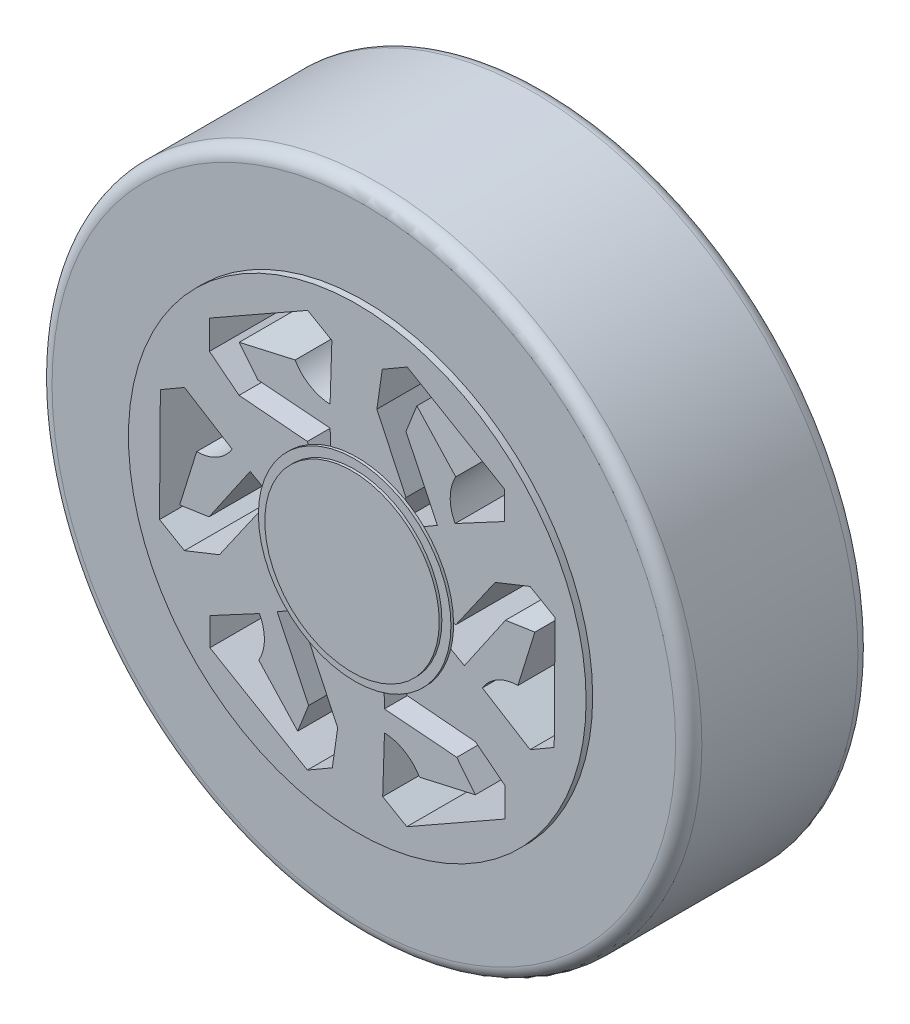
SolidWorks part; units mm, degrees
ref_plane "Front Plane" through (0, 0, 0) normal (0, 0, 1) x (1, 0, 0)
ref_plane "Top Plane" through (0, 0, 0) normal (0, 1, 0) x (1, 0, 0)
ref_plane "Right Plane" through (0, 0, 0) normal (1, 0, 0) x (0, 0, -1)
sketch "Sketch2" plane through (0, 0, 0) normal (0, 0, 1) x (1, 0, 0)
  circle A0 centre (0, 0) radius 247.55
  dimension "D1" = 495.1
extrude "Boss-Extrude1" add sketch "Sketch2" along normal blind 138.9
sketch "Sketch3" plane through (0, 0, 138.9) normal (0, 0, 1) x (1, 0, 0)
  circle A0 centre (0, 0) radius 174.35
  dimension "D1" = 348.7
fillet "Fillet1" radius 10 1 edges at (247.55, 0, 138.9)
fillet "Fillet2" radius 10 1 edges at (247.55, 0, 0)
extrude "Boss-Extrude2" add sketch "Sketch3" along normal blind 5
sketch "Sketch5" plane through (0, 0, 143.9) normal (0, 0, 1) x (1, 0, 0)
  line L0 (105.0037, 43.3694) -> (131.6337, 54.0214)
  line L1 (131.6337, 54.0214) -> (150.6653, 43.0319)
  line L2 (150.6653, 43.0319) -> (150.3446, -0.3609)
  line L3 (150.3446, -0.3609) -> (150.0291, -43.0412)
  line L4 (150.0291, -43.0412) -> (131.6404, -53.6579)
  line L5 (131.6404, -53.6579) -> (95.2902, -31.0843)
  line L7 (122.3632, -15.976) -> (135.2996, 25.6977)
  line L8 (135.2996, 25.6977) -> (112.9256, 22.3447)
  line L10 (112.9256, 22.3447) -> (81.5922, -23.3101)
  line L11 (81.5922, -23.3101) -> (40.2577, 0.1488)
  line L12 (40.2577, 0.1488) -> (75.1777, 0.5509)
  line L13 (75.1777, 0.5509) -> (105.0037, 43.3694)
  line L14 (90.0609, -69.2512) -> (112.6007, -86.9874)
  line L16 (112.6007, -86.9874) -> (112.5994, -108.964)
  line L17 (112.5994, -108.964) -> (74.8597, -130.3827)
  line L18 (74.8597, -130.3827) -> (37.7398, -151.4496)
  line L19 (37.7398, -151.4496) -> (19.3511, -140.8329)
  line L20 (19.3511, -140.8329) -> (20.7253, -98.0659)
  line L21 (47.346, -113.9577) -> (89.9046, -104.3241)
  line L22 (89.9046, -104.3241) -> (75.8138, -86.6241)
  line L23 (19.0329, 141.0088) -> (38.0659, 151.9959)
  line L24 (38.0659, 151.9959) -> (75.4849, 130.0217)
  line L25 (75.4849, 130.0217) -> (112.2893, 108.4084)
  line L26 (112.2893, 108.4084) -> (112.2893, 87.175)
  line L27 (112.2893, 87.175) -> (74.5649, 66.9816)
  line L28 (75.0173, 97.9817) -> (45.395, 130.0217)
  line L29 (45.395, 130.0217) -> (37.1117, 108.9688)
  line L30 (37.1117, 108.9688) -> (60.9833, 59.0059)
  line L31 (60.9833, 59.0059) -> (20, 34.9386)
  line L32 (20, 34.9386) -> (37.1117, 65.3813)
  line L33 (37.1117, 65.3813) -> (14.9428, 112.6206)
  line L34 (14.9428, 112.6206) -> (19.0329, 141.0088)
  line L35 (75.8138, -86.6241) -> (20.6089, -82.316)
  line L36 (20.6089, -82.316) -> (20.2577, -34.7898)
  line L37 (20.2577, -34.7898) -> (38.066, -64.8303)
  line L38 (38.066, -64.8303) -> (90.0609, -69.2512)
  line L39 (-14.9428, -112.6206) -> (-19.0329, -141.0088)
  line L40 (-19.0329, -141.0088) -> (-38.0659, -151.9959)
  line L41 (-38.0659, -151.9959) -> (-75.4849, -130.0217)
  line L42 (-75.4849, -130.0217) -> (-112.2893, -108.4084)
  line L43 (-112.2893, -108.4084) -> (-112.2893, -87.175)
  line L44 (-112.2893, -87.175) -> (-74.5649, -66.9816)
  line L45 (-75.0173, -97.9817) -> (-45.395, -130.0217)
  line L46 (-45.395, -130.0217) -> (-37.1117, -108.9687)
  line L47 (-37.1117, -108.9687) -> (-60.9833, -59.0059)
  line L48 (-60.9833, -59.0059) -> (-20, -34.9386)
  line L49 (-20, -34.9386) -> (-37.1117, -65.3812)
  line L50 (-37.1117, -65.3812) -> (-14.9428, -112.6206)
  line L51 (-105.0037, -43.3694) -> (-131.6337, -54.0214)
  line L52 (-131.6337, -54.0214) -> (-150.6653, -43.0319)
  line L53 (-150.6653, -43.0319) -> (-150.3446, 0.3609)
  line L54 (-150.3446, 0.3609) -> (-150.0291, 43.0412)
  line L55 (-150.0291, 43.0412) -> (-131.6404, 53.6579)
  line L56 (-131.6404, 53.6579) -> (-95.2902, 31.0843)
  line L57 (-122.3632, 15.976) -> (-135.2996, -25.6977)
  line L58 (-135.2996, -25.6977) -> (-112.9256, -22.3447)
  line L59 (-112.9256, -22.3447) -> (-81.5922, 23.3101)
  line L60 (-81.5922, 23.3101) -> (-40.2577, -0.1488)
  line L61 (-40.2577, -0.1488) -> (-75.1777, -0.5509)
  line L62 (-75.1777, -0.5509) -> (-105.0037, -43.3694)
  line L63 (-90.0609, 69.2512) -> (-112.6007, 86.9874)
  line L64 (-112.6007, 86.9874) -> (-112.5994, 108.964)
  line L65 (-112.5994, 108.964) -> (-74.8597, 130.3827)
  line L66 (-74.8597, 130.3827) -> (-37.7398, 151.4496)
  line L67 (-37.7398, 151.4496) -> (-19.3511, 140.8329)
  line L68 (-19.3511, 140.8329) -> (-20.7253, 98.0659)
  line L69 (-47.346, 113.9577) -> (-89.9046, 104.3241)
  line L70 (-89.9046, 104.3241) -> (-75.8138, 86.6241)
  line L71 (-75.8138, 86.6241) -> (-20.6089, 82.316)
  line L72 (-20.6089, 82.316) -> (-20.2577, 34.7898)
  line L73 (-20.2577, 34.7898) -> (-38.066, 64.8303)
  line L74 (-38.066, 64.8303) -> (-90.0609, 69.2512)
  arc A2 (74.5649, 66.9816) -> (75.0173, 97.9817) centre (102.7589, 82.0735) cw
  arc A3 (95.2902, -31.0843) -> (122.3632, -15.976) centre (122.4571, -47.955) cw
  arc A4 (20.7253, -98.0659) -> (47.346, -113.9577) centre (19.6983, -130.0285) cw
  arc A5 (-74.5649, -66.9816) -> (-75.0173, -97.9817) centre (-102.7589, -82.0735) cw
  arc A6 (-95.2902, 31.0843) -> (-122.3632, 15.976) centre (-122.4571, 47.955) cw
  arc A7 (-20.7253, 98.0659) -> (-47.346, 113.9577) centre (-19.6983, 130.0285) cw
  point P1 (0, 0)
  point P3 (0, 0)
  point P87 (0, 0)
  dimension "D1" = 6
sketch "Sketch6" plane through (0, 0, 143.9) normal (0, 0, 1) x (1, 0, 0)
sketch "Sketch8" plane through (0, 0, 143.9) normal (0, 0, 1) x (1, 0, 0)
extrude "Cut-Extrude1" cut sketch "Sketch5" against normal blind 178
sketch "Sketch9" plane through (0, 0, 143.9) normal (0, 0, 1) x (1, 0, 0)
  circle A0 centre (0, 0) radius 73.3512
extrude "Boss-Extrude3" add sketch "Sketch9" along normal blind 2
sketch "Sketch10" plane through (0, 0, 145.9) normal (0, 0, 1) x (1, 0, 0)
  circle A0 centre (0, 0) radius 66.4494
extrude "Boss-Extrude4" add sketch "Sketch10" along normal blind 2
